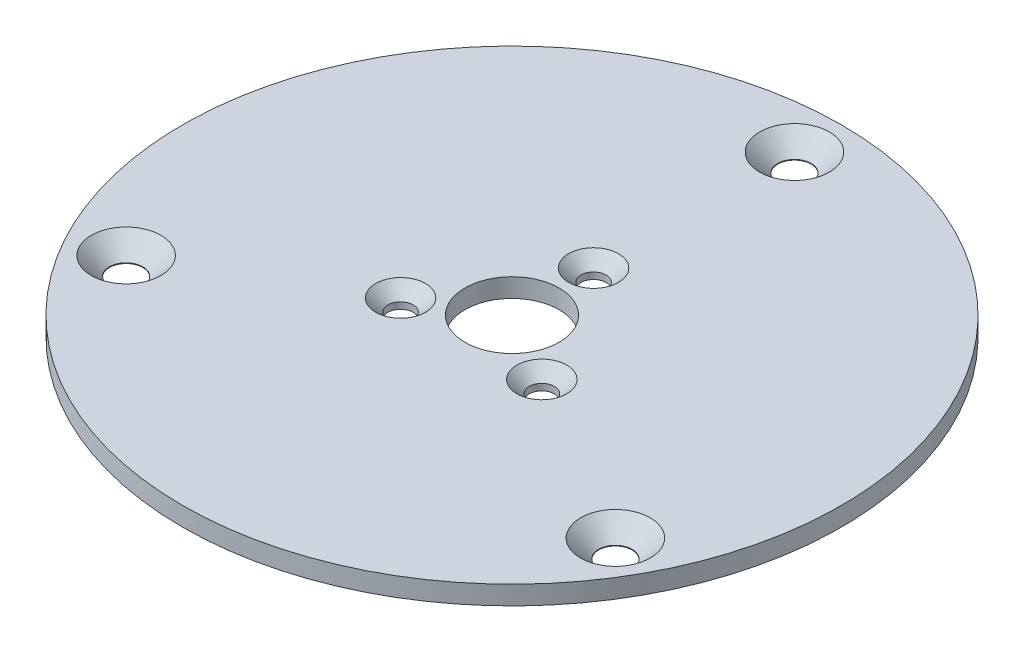
SolidWorks part; units mm, degrees
ref_plane "Front Plane" through (0, 0, 0) normal (0, 0, 1) x (1, 0, 0)
ref_plane "Top Plane" through (0, 0, 0) normal (0, 1, 0) x (1, 0, 0)
ref_plane "Right Plane" through (0, 0, 0) normal (1, 0, 0) x (0, 0, -1)
sketch "Sketch1" plane through (0, 0, 0) normal (0, 1, 0) x (1, 0, 0)
  circle A1 centre (0, 0) radius 44.45
  dimension "D2" = 88.9
extrude "Boss-Extrude1" add sketch "Sketch1" along normal blind 2.54
sketch "Sketch2" plane through (0, 0, 0) normal (0, 0, 1) x (1, 0, 0)
  line L0 (0, 6.2846) -> (0, -3.885) construction
sketch "Sketch7" plane through (0, 2.54, 0) normal (0, 1, 0) x (1, 0, 0)
  line L0 (0, 0) -> (0, 38.1) construction
  line L1 (0, 0) -> (32.9956, -19.05) construction
  line L2 (0, 0) -> (-32.9956, -19.05) construction
  point P10 (0, 0)
  dimension "D2" = 38.1
  dimension "D3" = 3
hole_wizard "CSK for M4 Flat Head Machine Screw1" positions "Sketch9" profile "Sketch8" countersink size "M4" standard "ANSI Metric" end condition through all
sketch "Sketch9" plane through (0, 2.54, 0) normal (0, 1, 0) x (1, 0, 0)
  point P0 (0, 38.1)
  point P3 (-32.9956, -19.05)
  point P6 (32.9956, -19.05)
sketch "Sketch8" plane through (0, 2.54, -38.1) normal (1, 0, 0) x (0, 0, 1)
  line L0 (0, 0) -> (0, 2.54)
  line L1 (0, 2.54) -> (2.25, 2.54)
  line L2 (2.25, 2.54) -> (2.25, 2.45)
  line L3 (2.25, 2.45) -> (4.7, 0)
  line L5 (4.7, 0) -> (0, 0)
  line L6 (-2.25, 2.45) -> (-4.7, 0) construction
  line L11 (0, -6.35) -> (0, 107.95) construction
  dimension "Thru Hole Dia." = 4.5
  dimension "Thru Hole Depth" = 2.54
  dimension "Near C'Sink Dia." = 9.4
  dimension "Near C'Sink Angle" = 90
sketch "Sketch10" plane through (0, 2.54, 0) normal (0, 1, 0) x (1, 0, 0)
  line L0 (0, 0) -> (-38.4948, 22.225) construction
  line L1 (0, 0) -> (0, -44.45) construction
  line L2 (0, 0) -> (38.4948, 22.225) construction
  circle A0 centre (0, 0) radius 44.45 construction
  dimension "D1" = 120
  dimension "D2" = 120
sketch "Sketch11" plane through (0, 2.54, 0) normal (0, 1, 0) x (1, 0, 0)
  circle A6 centre (0, 0) radius 6.35
  dimension "D4" = 12.7
extrude "Cut-Extrude1" cut sketch "Sketch11" against normal through all
sketch "Sketch12" plane through (0, 2.54, 0) normal (0, 1, 0) x (1, 0, 0)
  line L0 (-9.5263, -5.5) -> (0, 0) construction
  line L1 (0, 0) -> (0, 11) construction
  line L2 (0, 11) -> (9.5263, -5.5) construction
  line L3 (9.5263, -5.5) -> (0, 0) construction
  line L4 (0, 11) -> (-9.5263, -5.5) construction
  line L5 (-9.5263, -5.5) -> (9.5263, -5.5) construction
  point P0 (0, 11)
  point P1 (-9.5263, -5.5)
  point P2 (9.5263, -5.5)
  dimension "D1" = 11
hole_wizard "CSK for M3 SFHCS1" positions "Sketch14" profile "Sketch13" countersink size "M3" standard "ANSI Metric" end condition through all
sketch "Sketch14" plane through (0, 2.54, 0) normal (0, 1, 0) x (1, 0, 0)
  point P0 (0, 11)
  point P3 (-9.5263, -5.5)
  point P6 (9.5263, -5.5)
sketch "Sketch13" plane through (0, 2.54, -11) normal (1, 0, 0) x (0, 0, 1)
  line L0 (0, 0) -> (0, 2.54)
  line L1 (0, 2.54) -> (1.7, 2.54)
  line L2 (1.7, 2.54) -> (1.7, 1.66)
  line L3 (1.7, 1.66) -> (3.36, 0)
  line L5 (3.36, 0) -> (0, 0)
  line L6 (-1.7, 1.66) -> (-3.36, 0) construction
  line L11 (0, -6.35) -> (0, 107.95) construction
  dimension "Thru Hole Dia." = 3.4
  dimension "Thru Hole Depth" = 2.54
  dimension "Near C'Sink Dia." = 6.72
  dimension "Near C'Sink Angle" = 90
sketch "Sketch15" plane through (0, 2.54, 0) normal (0, 1, 0) x (1, 0, 0)
  circle A0 centre (0, 0) radius 11 construction
  circle A1 centre (0, 0) radius 38.1 construction
  circle A2 centre (0, 38.1) radius 2.25
  circle A3 centre (0, 11) radius 1.7
  circle A4 centre (0, 0) radius 6.35
  circle A5 centre (0, 11) radius 1.7 construction
  circle A6 centre (0, 38.1) radius 2.25 construction
  circle A7 centre (0, 0) radius 6.35 construction
